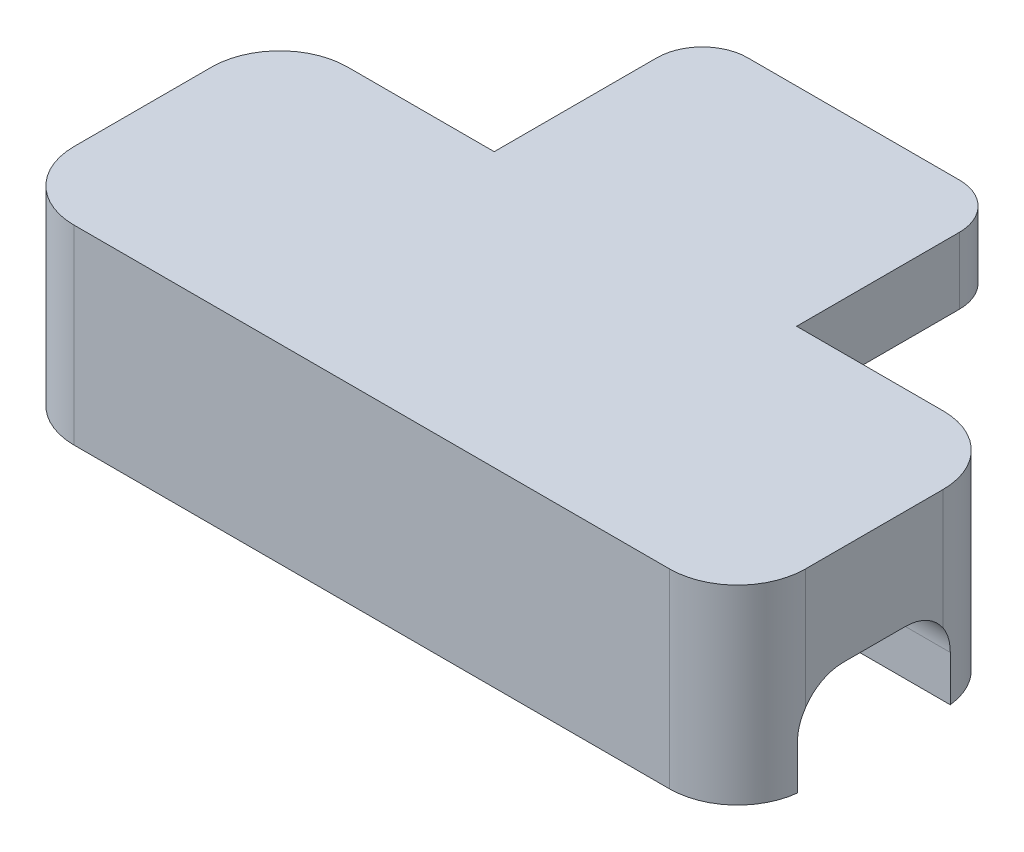
SolidWorks part; units mm, degrees
ref_plane "Front Plane" through (0, 0, 0) normal (0, 0, 1) x (1, 0, 0)
ref_plane "Top Plane" through (0, 0, 0) normal (0, 1, 0) x (1, 0, 0)
ref_plane "Right Plane" through (0, 0, 0) normal (1, 0, 0) x (0, 0, -1)
ref_plane "Plane3" through (0, 3.23, 0) normal (0, 1, 0) x (1, 0, 0)
sketch "Sketch21" plane through (0, 0, 0) normal (0, 1, 0) x (1, 0, 0)
  line L5 (0, 12) -> (-15.69, 12)
  line L6 (0, 12) -> (0, -12)
  line L7 (0, -12) -> (-15.69, -12)
  line L8 (-15.69, 12) -> (-15.69, -12)
  line L9 (17, 12) -> (32.69, 12)
  line L10 (17, 12) -> (17, -12)
  line L11 (17, -12) -> (32.69, -12)
  line L12 (32.69, 12) -> (32.69, -12)
  dimension "D2" = 17
  dimension "D3" = 24
  dimension "D5" = 15.69
  dimension "D6" = 15.69
extrude "Boss-Extrude1" add sketch "Sketch21" along normal blind 4.44 and the other way blind 6
sketch "Sketch20" plane through (0, 0, 0) normal (1, 0, 0) x (0, 0, -1)
  line L0 (13.2, 3.23) -> (-13.2, 3.23) construction
  line L1 (-5.7, -0.36) -> (-5.7, -3.36)
  line L2 (-2.7, 2.64) -> (0, 2.64)
  line L4 (-5.7, -3.36) -> (-9.7, -3.36)
  line L6 (0, 2.64) -> (1.4, 2.64)
  line L19 (4.4, -0.36) -> (4.4, -3.36)
  line L24 (-16.1319, -7.1274) -> (15.5779, -7.1274)
  line L26 (8.4, -3.36) -> (4.4, -3.36)
  line L28 (-16.1319, 6.5474) -> (15.5779, 6.5474)
  line L30 (-9.7, 4.14) -> (8.4, 4.14)
  line L32 (-9.7, 4.14) -> (-9.7, -3.36)
  line L33 (8.4, 4.14) -> (8.4, -3.36)
  line L36 (-16.1319, 6.5474) -> (-16.1319, -7.1274)
  line L37 (15.5779, -7.1274) -> (15.5779, 6.5474)
  line L38 (-2.7, 2.64) -> (-5.7, 2.64)
  line L39 (-5.7, 2.64) -> (-5.7, -0.36)
  line L40 (1.4, 2.64) -> (4.4, 2.64)
  line L41 (4.4, 2.64) -> (4.4, -0.36)
  dimension "D1" = 2.7
  dimension "D2" = 0.59
  dimension "D5" = 6
  dimension "D6" = 0.91
  dimension "D7" = 1.4
  dimension "D8" = 0
  dimension "D10" = 4
  dimension "D11" = 4
extrude "Cut-Extrude4" cut sketch "Sketch20" against normal through all both and the other way through all
ref_plane "Plane5" through (0, 7.74, 0) normal (0, 1, 0) x (1, 0, 0)
sketch "Sketch28" plane through (0, 7.74, 0) normal (0, 1, 0) x (1, 0, 0)
  line L5 (-1.5, 19.16) -> (-1.5, -1.34)
  line L7 (18.5, 19.16) -> (18.5, -1.34)
  line L9 (1.5, 22.16) -> (15.5, 22.16)
  line L10 (17, -9.7) -> (32.69, -9.7) construction
  line L12 (-1.5, -1.34) -> (-1.5, -9.7)
  line L13 (-1.5, -9.7) -> (18.5, -9.7)
  line L14 (18.5, -1.34) -> (18.5, -9.7)
  line L19 (-15.69, 8.4) -> (0, 8.4) construction
  arc A2 (15.5, 22.16) -> (18.5, 19.16) centre (15.5, 19.16) cw
  arc A3 (1.5, 22.16) -> (-1.5, 19.16) centre (1.5, 19.16) ccw
  point P6 (-1.5, 23.96)
  point P7 (-1.5, -3.04)
  point P8 (18.5, -3.04)
  point P9 (18.5, 23.96)
  point P25 (17, 22.46)
  dimension "D1" = 13.76
extrude "Boss-Extrude4" add sketch "Sketch28" along normal blind 1.5 separate body
sketch "Sketch26" plane through (0, 7.74, 0) normal (0, 1, 0) x (1, 0, 0)
  line L0 (17, 8.4) -> (32.69, 8.4) construction
  line L1 (2.75, 21.16) -> (14.25, 21.16)
  line L2 (-0.25, 18.16) -> (-0.25, -0.4)
  line L3 (2.75, -3.4) -> (14.25, -3.4)
  line L4 (17.25, 18.16) -> (17.25, -0.4)
  line L5 (-1.5, 19.16) -> (-1.5, -0.04)
  line L7 (18.5, 19.16) -> (18.5, -1.9)
  line L9 (1.5, 22.16) -> (15.5, 22.16)
  line L10 (-1.5, -4.65) -> (18.5, -4.65) construction
  line L11 (-1.5, 22.41) -> (18.5, 22.41) construction
  line L12 (-1.5, 22.41) -> (-1.5, -4.65) construction
  line L13 (18.5, 22.41) -> (18.5, -4.65) construction
  line L14 (17.25, 21.16) -> (17.25, -3.4) construction
  line L15 (-0.25, 21.16) -> (17.25, 21.16) construction
  line L16 (-0.25, -3.4) -> (17.25, -3.4) construction
  line L17 (-0.25, 21.16) -> (-0.25, -3.4) construction
  line L20 (18.5, -1.9) -> (18.5, -9.7)
  line L21 (18.5, -9.7) -> (-1.5, -9.7)
  line L22 (-1.5, -0.04) -> (-1.5, -9.7)
  arc A2 (15.5, 22.16) -> (18.5, 19.16) centre (15.5, 19.16) cw
  arc A3 (1.5, 22.16) -> (-1.5, 19.16) centre (1.5, 19.16) ccw
  arc A4 (17.25, 18.16) -> (14.25, 21.16) centre (14.25, 18.16) ccw
  arc A5 (14.25, -3.4) -> (17.25, -0.4) centre (14.25, -0.4) ccw
  arc A6 (-0.25, -0.4) -> (2.75, -3.4) centre (2.75, -0.4) ccw
  arc A7 (-0.25, 18.16) -> (2.75, 21.16) centre (2.75, 18.16) cw
  point P25 (17.25, 21.16)
  dimension "D7" = 3
  dimension "D1" = 11.5
  dimension "D2" = 12.76
  dimension "D3" = 11.8
  dimension "D5" = 1
  dimension "D4" = 1.25
extrude "Boss-Extrude5" add sketch "Sketch26" against normal up to surface (4.51 mm away) up to plane "Plane3"
sketch "Sketch24" plane through (0, 0, 0) normal (0, 1, 0) x (1, 0, 0)
  line L0 (-15.69, -9.7) -> (-1.5, -9.7) construction
  line L1 (-15.69, 8.4) -> (-11.19, 8.4)
  line L2 (-15.69, 8.4) -> (-15.69, -9.7)
  line L3 (-15.69, -9.7) -> (-11.19, -9.7)
  line L10 (0, 0) -> (8.5, 0) construction
  line L11 (-11.19, 8.4) -> (-8.19, 8.4)
  line L14 (-8.19, 8.4) -> (-8.19, 4.4)
  line L19 (8.5, 8.4) -> (8.5, -9.7) construction
  line L20 (-11.19, -9.7) -> (-8.19, -9.7)
  line L23 (-8.19, -9.7) -> (-8.19, -5.7)
  line L25 (-8.19, 4.4) -> (-11.19, 4.4)
  line L26 (-8.19, 4.4) -> (-8.19, -5.7)
  line L27 (-8.19, -5.7) -> (-11.19, -5.7)
  line L28 (-11.19, 4.4) -> (-11.19, -5.7)
  dimension "D1" = 4.5
  dimension "D2" = 8.5
  dimension "D3" = 3
  dimension "D4" = 4
  dimension "D5" = 4
extrude "Boss-Extrude2" add sketch "Sketch24" against normal up to surface and the other way up to surface up to face at (-7.845, -3.36, -6.4) other way up to face at (-0.1405, 4.14, -3.697)
ref_plane "Plane4" through (0, 0, 9.7) normal (0, 0, 1) x (1, 0, 0)
sketch "Sketch25" plane through (0, 0, 9.7) normal (0, 0, 1) x (1, 0, 0)
  line L0 (-15.69, 4.14) -> (-1.5, 4.14) construction
  line L1 (-15.69, -3.36) -> (-11.19, -3.36)
  line L2 (-15.69, -3.36) -> (-15.69, 4.14)
  line L3 (-15.69, 4.14) -> (-11.19, 4.14)
  line L4 (-11.19, -3.36) -> (-11.19, 0.2422)
  line L5 (-8.19, 3.2422) -> (-8.19, 4.14)
  line L6 (-11.19, 4.14) -> (-8.19, 4.14)
  line L12 (-11.19, 0.2422) -> (-11.19, 3.2422)
  line L13 (-11.19, 3.2422) -> (-8.19, 3.2422)
  dimension "D1" = 4.5
extrude "Boss-Extrude3" add sketch "Sketch25" against normal up to surface (18.1 mm away) up to face at (-4.36, 2.0375, -8.4)
fillet "Fillet1" radius 3 5 edges at (-5.595, 2.64, 5.7) (-5.595, 2.64, -4.4) (-11.19, 2.64, 0.65) (-11.19, -0.36, -4.4) (-11.19, -0.36, 5.7)
fillet "Fillet2" radius 3 2 edges at (24.845, 2.64, -4.4) (24.845, 2.64, 5.7)
sketch "Sketch29" plane through (-0.25, 0, 0) normal (1, 0, 0) x (0, 0, -1)
  line L1 (-5.7, -0.36) -> (-5.7, -3.36)
  line L2 (-2.7, 2.64) -> (0, 2.64)
  line L4 (-5.7, -3.36) -> (-9.7, -3.36)
  line L6 (0, 2.64) -> (1.4, 2.64)
  line L19 (4.4, -0.36) -> (4.4, -3.36)
  line L26 (8.4, -3.36) -> (4.4, -3.36)
  line L30 (-9.7, 4.14) -> (8.4, 4.14)
  line L32 (-9.7, 4.14) -> (-9.7, -3.36)
  line L33 (8.4, 4.14) -> (8.4, -3.36)
  line L42 (1.4, 2.64) -> (1.4, -0.36) construction
  arc A0 (-5.7, -0.36) -> (-2.7, 2.64) centre (-2.7, -0.36) cw
  arc A1 (4.4, -0.36) -> (1.4, 2.64) centre (1.4, -0.36) ccw
  dimension "D1" = 2.7
  dimension "D5" = 6
  dimension "D7" = 1.4
  dimension "D10" = 4
  dimension "D11" = 4
extrude "Cut-Extrude5" cut sketch "Sketch29" along normal offset from surface 1 and the other way blind 1 up to face at (17.25, 5.0367, -8.72) offset beyond the face yes
sketch "Sketch30" plane through (0, 3.23, 0) normal (0, 1, 0) x (1, 0, 0)
  line L0 (-6.93, -9.7) -> (6.93, -9.7) construction
  line L1 (-15.69, 8.4) -> (-1.5, 8.4)
  line L2 (-15.69, 8.4) -> (-15.69, -9.7)
  line L3 (-15.69, -9.7) -> (-1.5, -9.7)
  line L4 (-1.5, 8.4) -> (-1.5, -9.7)
  line L5 (18.5, -9.7) -> (18.5, 19.16) construction
  line L6 (32.69, 8.4) -> (18.5, 8.4)
  line L7 (32.69, 8.4) -> (32.69, -9.7)
  line L8 (32.69, -9.7) -> (18.5, -9.7)
  line L9 (18.5, 8.4) -> (18.5, -9.7)
extrude "Boss-Extrude6" add sketch "Sketch30" along normal up to surface (6.01 mm away) up to face at (8.5, 9.24, -10.7471)
sketch "Sketch31" plane through (0, 3.23, 0) normal (0, 1, 0) x (1, 0, 0)
  line L0 (-6.93, -9.7) -> (6.93, -9.7) construction
  line L1 (-1.25, -7.7) -> (18.25, -7.7)
  line L2 (-1.25, -7.7) -> (-1.25, -9.7)
  line L3 (-1.25, -9.7) -> (18.25, -9.7)
  line L4 (18.25, -7.7) -> (18.25, -9.7)
  dimension "D1" = 19.5
  dimension "D2" = 2
  dimension "D3" = 18.25
extrude "Boss-Extrude7" add sketch "Sketch31" against normal up to surface and the other way through all up to face at (25.47, -3.36, 7.7)
ref_plane "Plane6" through (0, 0, -22.16) normal (0, 0, -1) x (-1, 0, 0)
sketch "Sketch33" plane through (0, 0, -22.16) normal (0, 0, -1) x (-1, 0, 0)
  line L0 (15.69, 4.83) -> (15.69, -3.36)
  line L5 (-13.1, 4.83) -> (-13.1, 4.94)
  line L6 (55, 7.74) -> (-55, 7.74) construction
  line L7 (15.69, -3.36) -> (-32.69, -3.36)
  line L8 (-32.69, 9.24) -> (-18.5, 9.24) construction
  line L14 (-32.69, 4.83) -> (-32.69, -3.36)
  line L29 (-32.69, 4.83) -> (-13.1, 4.83)
  line L31 (-3.9, 4.83) -> (15.69, 4.83)
  line L37 (-3.9, 4.83) -> (-3.9, 4.94)
  line L38 (-11.8, 6.24) -> (-5.2, 6.24)
  arc A6 (-11.8, 6.24) -> (-13.1, 4.94) centre (-11.8, 4.94) ccw
  arc A7 (-5.2, 6.24) -> (-3.9, 4.94) centre (-5.2, 4.94) cw
  point P5 (-8.5, 6.24)
  point P7 (-8.5, -3.36)
  dimension "D1" = 1.5
  dimension "D2" = 1.5
  dimension "D3" = 2.91
  dimension "D4" = 6.6
  dimension "D5" = 0
extrude "Cut-Extrude6" cut sketch "Sketch33" against normal up to surface (13.76 mm away) up to face at (23.1467, 3.0367, -8.4)
fillet "Fillet3" radius 4.5 4 edges at (32.69, 2.94, -8.4) (32.69, 2.94, 9.7) (-15.69, 2.94, -8.4) (-15.69, 2.94, 9.7)
sketch "Sketch35" plane through (0, 7.74, 0) normal (0, -1, 0) x (1, 0, 0)
  line L0 (2.75, 3.4) -> (14.25, 3.4) construction
  line L1 (2.5, 3.4) -> (14.5, 3.4)
  line L2 (2.5, 3.4) -> (2.5, -1.6)
  line L3 (2.5, -1.6) -> (14.5, -1.6)
  line L4 (14.5, 3.4) -> (14.5, -1.6)
  line L5 (14.25, -21.16) -> (2.75, -21.16) construction
  point P6 (8.5, 3.4)
  point P9 (8.5, -21.16)
  dimension "D1" = 12
  dimension "D2" = 5
  dimension "D3" = 0
  dimension "D4" = 0
extrude "Cut-Extrude7" cut sketch "Sketch35" against normal blind 0.7
